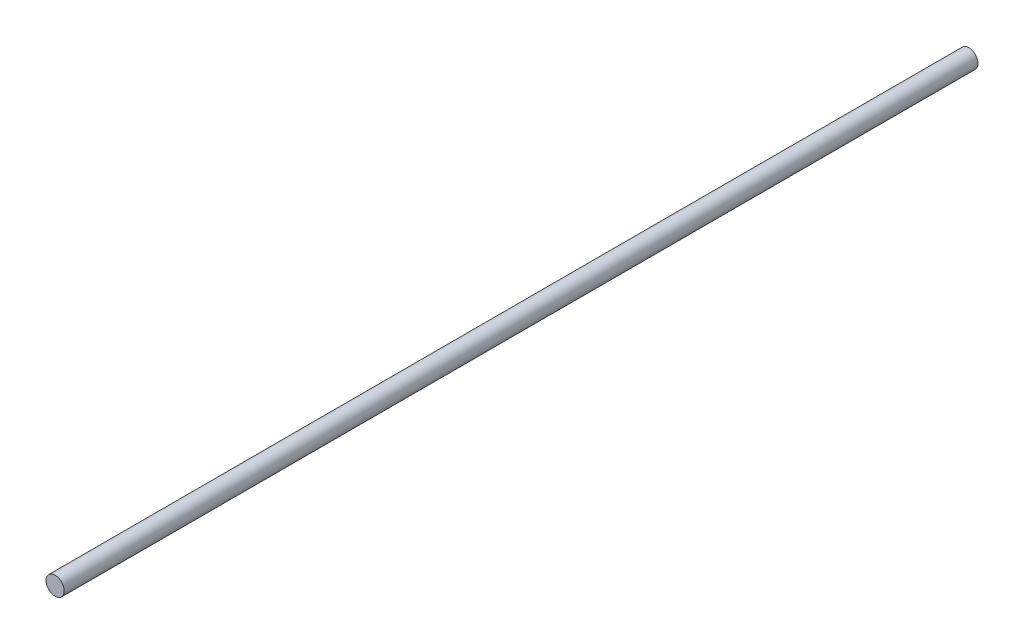
SolidWorks part; units mm, degrees
ref_plane "正面" through (0, 0, 0) normal (0, 0, 1) x (1, 0, 0)
ref_plane "平面" through (0, 0, 0) normal (0, 1, 0) x (1, 0, 0)
ref_plane "右側面" through (0, 0, 0) normal (1, 0, 0) x (0, 0, -1)
sketch "ｽｹｯﾁ1" plane through (0, 0, 0) normal (0, 0, 1) x (1, 0, 0)
  circle A0 centre (0, 0) radius 15
  dimension "D1" = 30
extrude "ﾎﾞｽ - 押し出し1" add sketch "ｽｹｯﾁ1" along normal blind 1500
